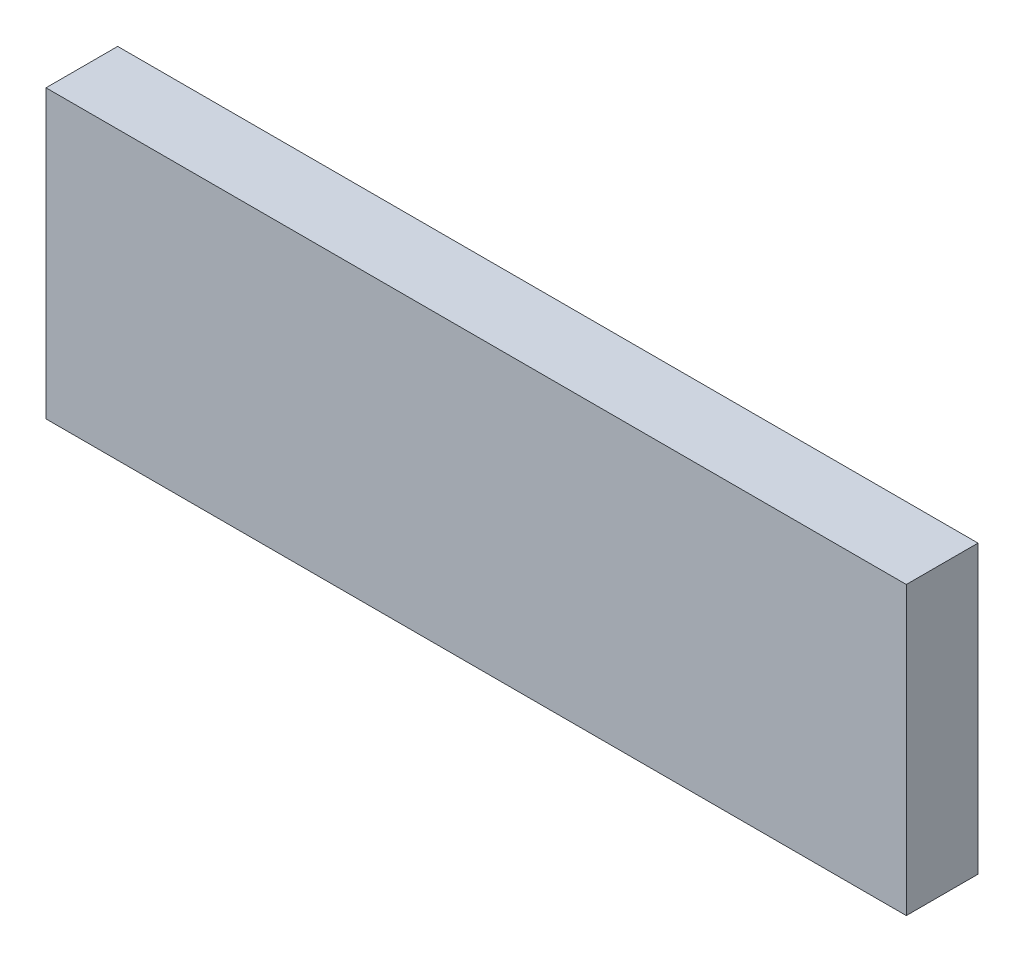
SolidWorks part; units mm, degrees
material "Pine"
ref_plane "Front Plane" through (0, 0, 0) normal (0, 0, 1) x (1, 0, 0)
ref_plane "Top Plane" through (0, 0, 0) normal (0, 1, 0) x (1, 0, 0)
ref_plane "Right Plane" through (0, 0, 0) normal (1, 0, 0) x (0, 0, -1)
sketch "Sketch1" plane through (0, 0, 0) normal (0, 0, 1) x (1, 0, 0)
  line L1 (-76.2, -25.4) -> (76.2, -25.4)
  line L2 (-76.2, -25.4) -> (-76.2, 25.4)
  line L3 (-76.2, 25.4) -> (76.2, 25.4)
  line L4 (76.2, -25.4) -> (76.2, 25.4)
  line L5 (-76.2, -25.4) -> (76.2, 25.4) construction
  line L6 (-76.2, 25.4) -> (76.2, -25.4) construction
  point P0 (0, 0)
  dimension "D1" = 152.4
  dimension "D2" = 50.8
extrude "Boss-Extrude1" add sketch "Sketch1" along normal blind 12.7
